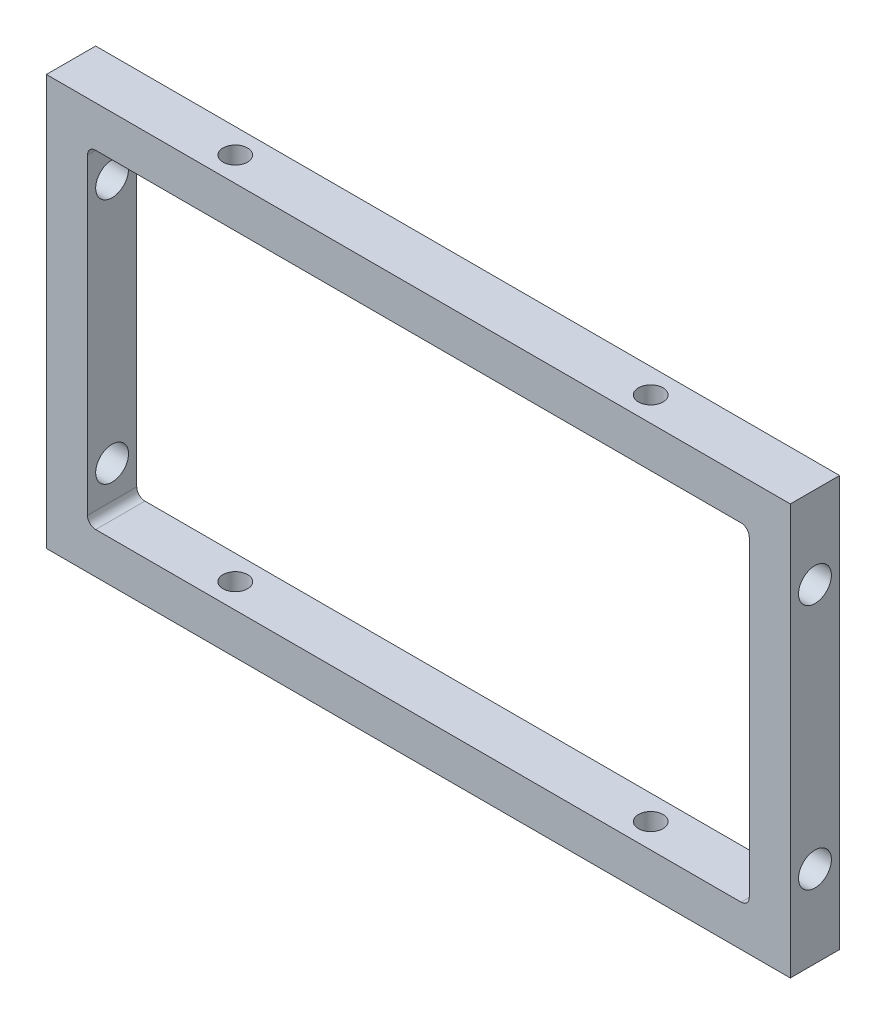
SolidWorks part; units mm, degrees
material "6061 合金"
ref_plane "前视基准面" through (0, 0, 0) normal (0, 0, 1) x (1, 0, 0)
ref_plane "上视基准面" through (0, 0, 0) normal (0, 1, 0) x (1, 0, 0)
ref_plane "右视基准面" through (0, 0, 0) normal (1, 0, 0) x (0, 0, -1)
sketch "草图1" plane through (0, 0, 0) normal (0, 0, 1) x (1, 0, 0)
  line L1 (-45.3, 25) -> (45.3, 25)
  line L2 (-45.3, 25) -> (-45.3, -25)
  line L3 (-45.3, -25) -> (45.3, -25)
  line L4 (45.3, 25) -> (45.3, -25)
  line L5 (-45.3, 25) -> (45.3, -25) construction
  line L6 (-45.3, -25) -> (45.3, 25) construction
  line L7 (-40.3, 20) -> (40.3, 20)
  line L8 (-40.3, 20) -> (-40.3, -20)
  line L9 (-40.3, -20) -> (40.3, -20)
  line L10 (40.3, 20) -> (40.3, -20)
  line L11 (-40.3, 20) -> (40.3, -20) construction
  line L12 (-40.3, -20) -> (40.3, 20) construction
  point P0 (0, 0)
  point P6 (0, 0)
  dimension "D1" = 50
  dimension "D2" = 5
  dimension "D3" = 5
  dimension "D4" = 90.6
extrude "凸台-拉伸1" add sketch "草图1" along normal blind 6
fillet "圆角1" radius 1 4 edges at (-40.3, -20, 3) (-40.3, 20, 3) (40.3, 20, 3) (40.3, -20, 3)
sketch "草图2" plane through (45.3, 0, 0) normal (1, 0, 0) x (0, 0, -1)
  line L0 (-14.6026, 0) -> (20.9478, 0) construction
  line L1 (-3, 25) -> (-3, -25) construction
  line L2 (-6, -25) -> (0, -25) construction
  circle A2 centre (-3, 15) radius 2
  circle A3 centre (-3, -15) radius 2
  dimension "D1" = 4
  dimension "D2" = 30
extrude "切除-拉伸1" cut sketch "草图2" against normal through all
sketch "草图3" plane through (0, 25, 0) normal (0, 1, 0) x (1, 0, 0)
  line L0 (-45.3, -3) -> (45.3, -3) construction
  line L1 (-45.3, -6) -> (-45.3, 0) construction
  line L2 (45.3, -6) -> (45.3, 0) construction
  line L3 (0, 0) -> (0, -21.2117) construction
  circle A0 centre (-25.3, -3) radius 1.5
  circle A1 centre (25.3, -3) radius 1.5
  dimension "D1" = 3
  dimension "D2" = 50.6
  dimension "D3" = 20
extrude "切除-拉伸2" cut sketch "草图3" against normal through all
